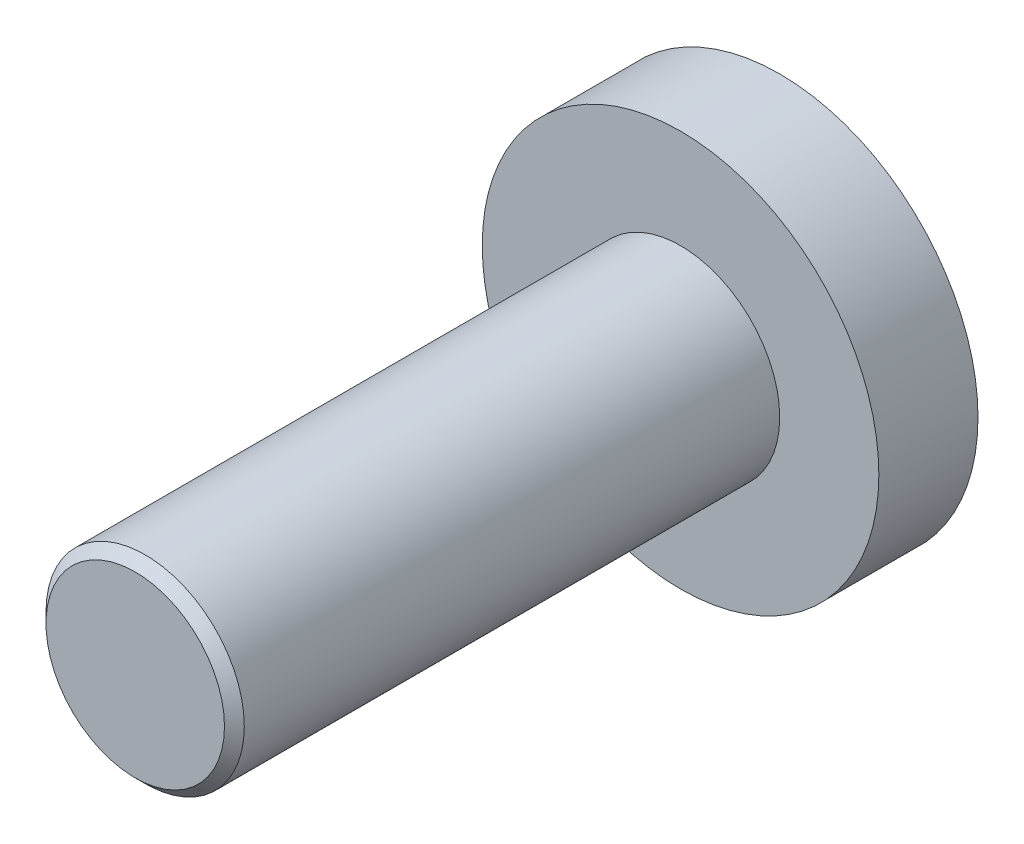
SolidWorks part; units mm, degrees
material "AISI 1020"
ref_plane "前视基准面" through (0, 0, 0) normal (0, 0, 1) x (1, 0, 0)
ref_plane "上视基准面" through (0, 0, 0) normal (0, 1, 0) x (1, 0, 0)
ref_plane "右视基准面" through (0, 0, 0) normal (1, 0, 0) x (0, 0, -1)
sketch "草图1" plane through (0, 0, 0) normal (0, 0, 1) x (1, 0, 0)
  circle A0 centre (0, 0) radius 2
  dimension "D1" = 4
extrude "拉伸1" add sketch "草图1" along normal blind 11
sketch "草图2" plane through (0, 0, 0) normal (0, 0, -1) x (-1, 0, 0)
  circle A0 centre (0, 0) radius 4
  dimension "D1" = 8
extrude "拉伸2" add sketch "草图2" along normal blind 2
chamfer "倒角1" distance 0.2 angle 45 1 edges at (2, 0, 11)
